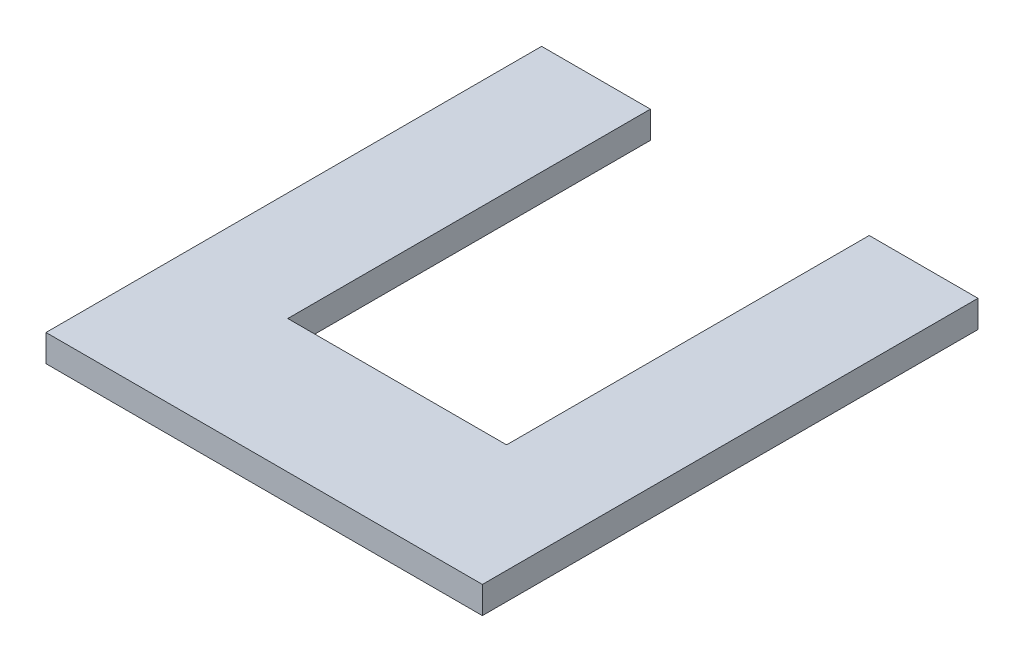
SolidWorks part; units mm, degrees
ref_plane "Alzado" through (0, 0, 0) normal (0, 0, 1) x (1, 0, 0)
ref_plane "Planta" through (0, 0, 0) normal (0, 1, 0) x (1, 0, 0)
ref_plane "Vista lateral" through (0, 0, 0) normal (1, 0, 0) x (0, 0, -1)
sketch "Croquis1" plane through (0, 0, 0) normal (0, 1, 0) x (1, 0, 0)
  line L0 (80.6273, 91.567) -> (0, 91.567)
  line L1 (80.6273, 91.567) -> (80.6273, 0)
  line L2 (80.6273, 0) -> (0, 0)
  line L3 (0, 91.567) -> (0, 0)
  line L4 (20.0991, 91.567) -> (60.5288, 91.567)
  line L5 (20.0991, 91.567) -> (20.0991, 24.567)
  line L6 (20.0991, 24.567) -> (60.5288, 24.567)
  line L7 (60.5288, 91.567) -> (60.5288, 24.567)
  point P8 (0, 0)
  dimension "D1" = 67
  dimension "D2" = 91.567
  dimension "D3" = 80.6273
  dimension "D4" = 20.0986
  dimension "D5" = 20.0991
extrude "Saliente-Extruir1" add sketch "Croquis1" along normal blind 5 contours L0 L7 L6 L5 L3 L2 L1
